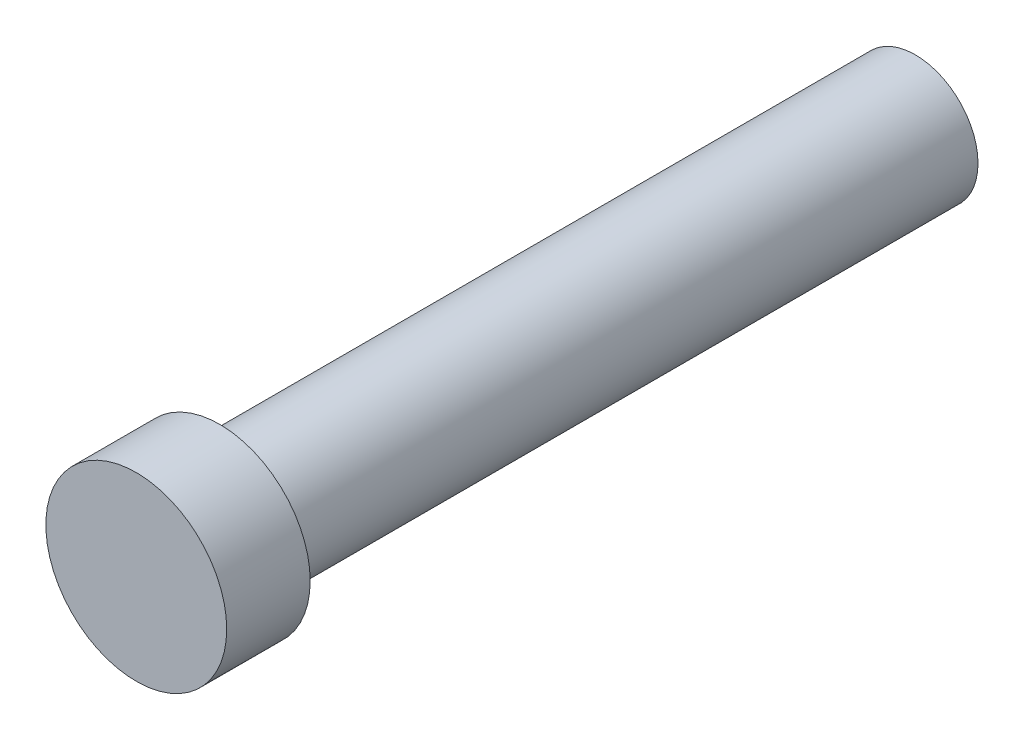
SolidWorks part; units mm, degrees
ref_plane "Plan de face" through (0, 0, 0) normal (0, 0, 1) x (1, 0, 0)
ref_plane "Plan de dessus" through (0, 0, 0) normal (0, 1, 0) x (1, 0, 0)
ref_plane "Plan de droite" through (0, 0, 0) normal (1, 0, 0) x (0, 0, -1)
sketch "Esquisse1" plane through (0, 0, 0) normal (0, 0, 1) x (1, 0, 0)
  circle A0 centre (0, 0) radius 2.25
  dimension "D1" = 4.5
extrude "Extru.-Mince1" add sketch "Esquisse1" along normal blind 25 thin thin type one direction reverse wall 1
ref_plane "Plan1" through (0, 0, 12.5) normal (0, 0, -1) x (-1, 0, 0)
sketch "Esquisse2" plane through (0, 0, 12.5) normal (0, 0, -1) x (-1, 0, 0)
  circle A0 centre (0, 0) radius 1.25 construction
  circle A1 centre (0, 0) radius 1.25
extrude "Boss.-Extru.1" add sketch "Esquisse2" along normal up to surface and the other way up to surface up to face at (2.25, 0, 0) other way up to face at (2.25, 0, 25)
sketch "Esquisse3" plane through (0, 0, 25) normal (0, 0, 1) x (1, 0, 0)
  circle A0 centre (0, 0) radius 3.25
  circle A1 centre (0, 0) radius 2.25
  circle A2 centre (0, 0) radius 2.25 construction
  dimension "D1" = 0
  dimension "D2" = 1
extrude "Boss.-Extru.2" add sketch "Esquisse3" along normal blind 3 contours A0
